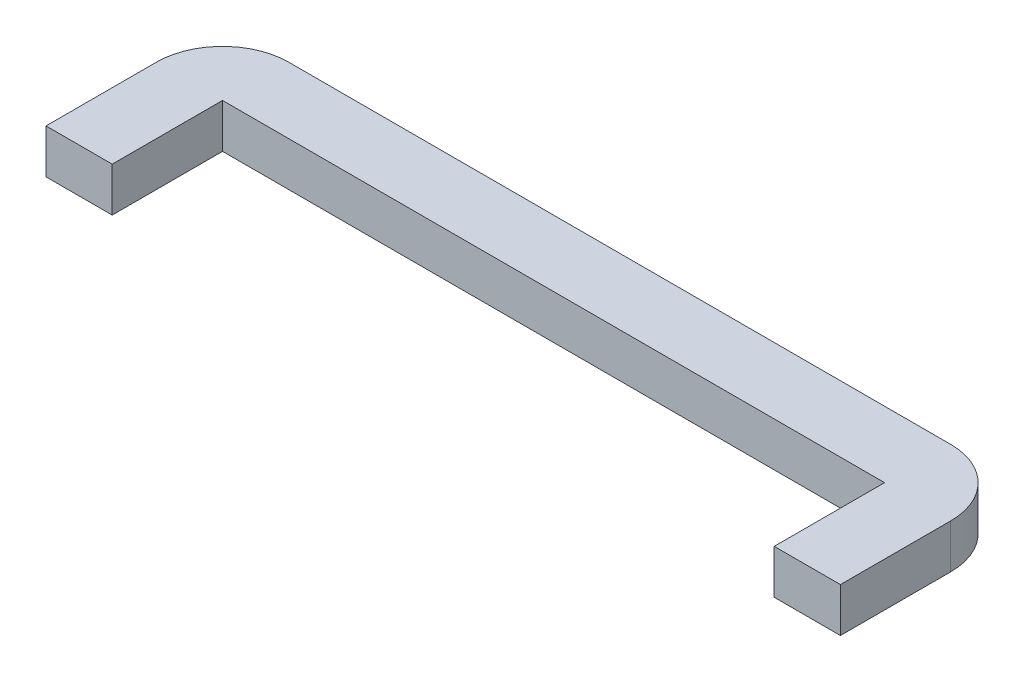
SolidWorks part; units mm, degrees
ref_plane "Front Plane" through (0, 0, 0) normal (0, 0, 1) x (1, 0, 0)
ref_plane "Top Plane" through (0, 0, 0) normal (0, 1, 0) x (1, 0, 0)
ref_plane "Right Plane" through (0, 0, 0) normal (1, 0, 0) x (0, 0, -1)
sketch "Sketch1" plane through (0, 0, 0) normal (0, 1, 0) x (1, 0, 0)
  line L1 (-18, -1.5) -> (18, -1.5)
  line L2 (-18, -1.5) -> (-18, 1.5)
  line L3 (-18, 1.5) -> (18, 1.5)
  line L4 (18, -1.5) -> (18, 1.5)
  line L5 (-18, -1.5) -> (18, 1.5) construction
  line L6 (-18, 1.5) -> (18, -1.5) construction
  line L7 (-18, -1.5) -> (-15, -1.5)
  line L8 (-18, -1.5) -> (-18, -6.5)
  line L9 (-18, -6.5) -> (-15, -6.5)
  line L10 (-15, -1.5) -> (-15, -6.5)
  line L11 (18, -1.5) -> (15, -1.5)
  line L12 (18, -1.5) -> (18, -6.5)
  line L13 (18, -6.5) -> (15, -6.5)
  line L14 (15, -1.5) -> (15, -6.5)
  point P0 (0, 0)
  dimension "D1" = 3
  dimension "D2" = 30
  dimension "D3" = 3
  dimension "D4" = 5
extrude "Boss-Extrude1" add sketch "Sketch1" along normal mid plane 2 contours L1 L4 L3 L2 | L10 L1 L8 L9 | L1 L14 L13 L12
fillet "Fillet1" radius 3 2 edges at (-18, 0, -1.5) (18, 0, -1.5)
